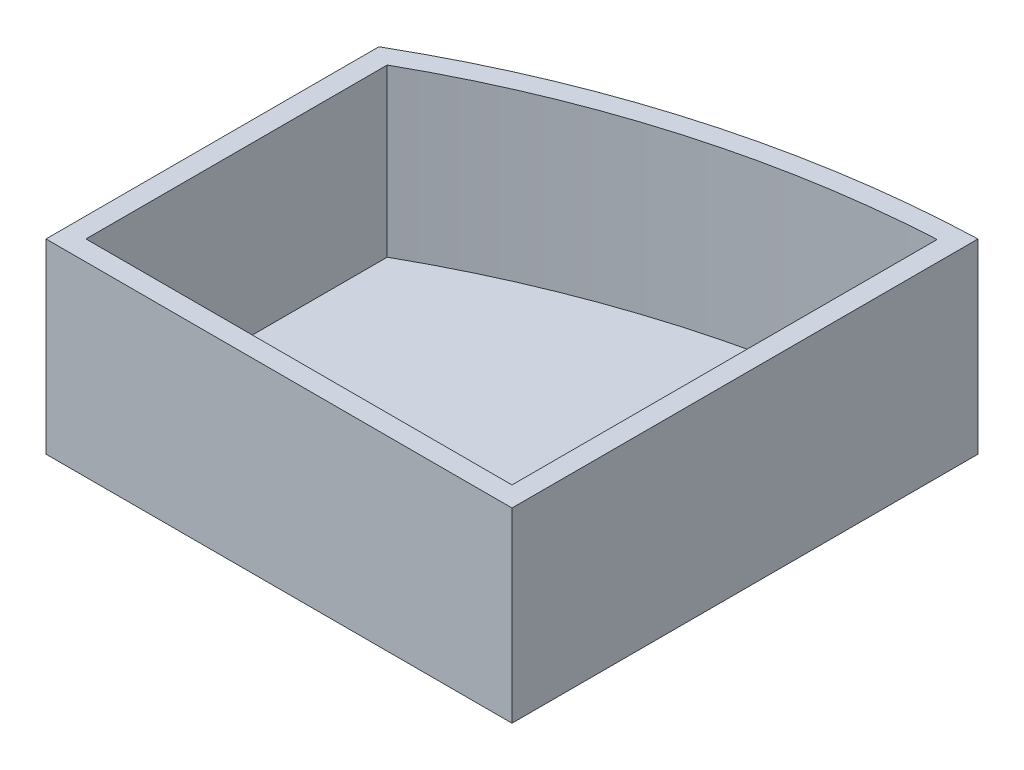
SolidWorks part; units mm, degrees
ref_plane "Front Plane" through (0, 0, 0) normal (0, 0, 1) x (1, 0, 0)
ref_plane "Top Plane" through (0, 0, 0) normal (0, 1, 0) x (1, 0, 0)
ref_plane "Right Plane" through (0, 0, 0) normal (1, 0, 0) x (0, 0, -1)
sketch "Sketch1" plane through (0, 0, 0) normal (0, 1, 0) x (1, 0, 0)
  line L0 (0, 0) -> (0, -70)
  line L1 (0, -70) -> (-70, -70)
  line L2 (-70, -70) -> (-70, -20)
  arc A1 (0, 0) -> (-70, -20) centre (4.9764, -149.9174) ccw
  dimension "D1" = 300
  dimension "D2" = 70
  dimension "D3" = 70
  dimension "D4" = 50
extrude "Boss-Extrude1" add sketch "Sketch1" along normal blind 3
sketch "Sketch2" plane through (0, 3, 0) normal (0, 1, 0) x (1, 0, 0)
  line L3 (-70, -70) -> (0, -70) construction
  line L4 (0, -70) -> (0, 0) construction
  line L5 (-70, -20) -> (-70, -70) construction
  line L6 (-67, -21.7441) -> (-67, -67)
  line L7 (-67, -67) -> (-3, -67)
  line L8 (-3, -67) -> (-3, -3.134)
  line L9 (-67, -21.7441) -> (-67, -67)
  line L10 (-67, -67) -> (-3, -67)
  line L11 (-3, -67) -> (-3, -3.134)
  line L12 (-70, -70) -> (0, -70)
  line L13 (0, -70) -> (0, 0)
  line L14 (-70, -20) -> (-70, -70)
  arc A1 (0, 0) -> (-70, -20) centre (4.9764, -149.9174) ccw construction
  arc A2 (-3, -3.134) -> (-67, -21.7441) centre (4.9764, -149.9174) ccw
  arc A3 (-3, -3.134) -> (-67, -21.7441) centre (4.9764, -149.9174) ccw
  arc A4 (0, 0) -> (-70, -20) centre (4.9764, -149.9174) ccw
  dimension "D1" = 3
extrude "Boss-Extrude2" add sketch "Sketch2" along normal blind 25
ref_plane "Plane1" through (0, 14, 0) normal (0, 1, 0) x (1, 0, 0)
sketch "Sketch3" plane through (0, 14, 0) normal (0, 1, 0) x (1, 0, 0)
  arc A0 (0, 0) -> (-70, -20) centre (4.9764, -149.9174) ccw construction
  arc A1 (0, 0) -> (-70, -20) centre (4.9764, -149.9174) ccw
ref_point "Point1" parameters "D1"=10
ref_plane "Plane2" through (-61.1787, 14, 15.2939) normal (-0.441, 0, -0.8975) x (-0.8975, 0, 0.441)
sketch "Sketch4" plane through (-61.1787, 14, 15.2939) normal (-0.441, 0, -0.8975) x (-0.8975, 0, 0.441)
  line L0 (9.9926, 0) -> (-61.6524, 0) construction
  circle A0 centre (-25.8299, 0) radius 2.5
  dimension "D1" = 5
extrude "Boss-Extrude3" add sketch "Sketch4" along normal blind 7 and the other way up to next
